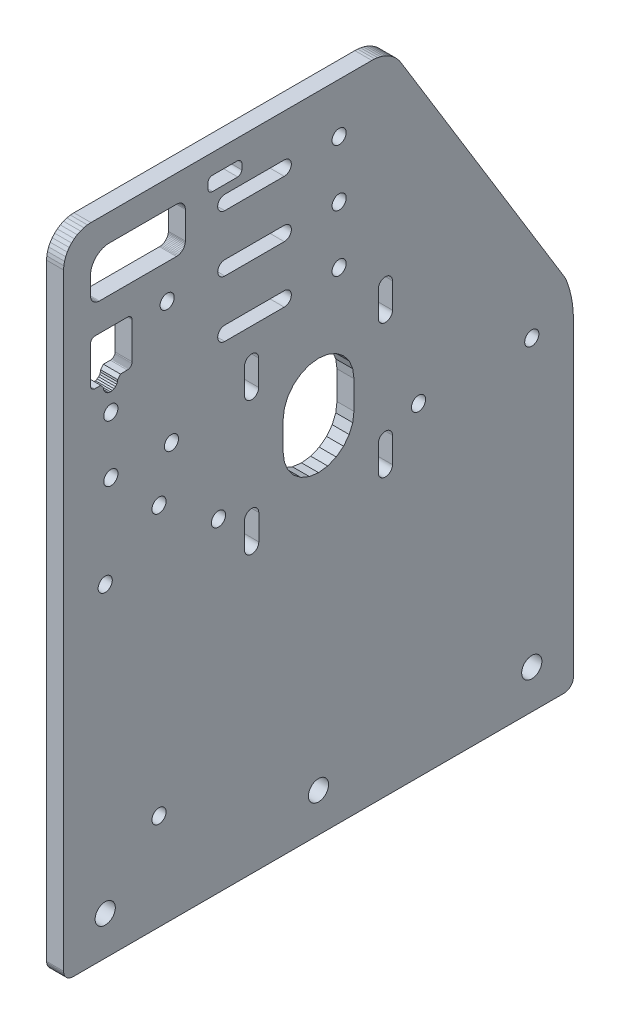
SolidWorks part; units mm, degrees
ref_plane "Front Plane" through (0, 0, 0) normal (0, 0, 1) x (1, 0, 0)
ref_plane "Top Plane" through (0, 0, 0) normal (0, 1, 0) x (1, 0, 0)
ref_plane "Right Plane" through (0, 0, 0) normal (1, 0, 0) x (0, 0, -1)
ref_plane "Plane1" through (0, 0, 0) normal (-1, 0, 0) x (0, -1, 0)
sketch "Sketch1" plane through (0, 0, 0) normal (-1, 0, 0) x (0, -1, 0)
  line L0 (-590.2121, -1614.2437) -> (-495.2304, -1672.3356)
  line L1 (-495.2304, -1672.3356) -> (-492.9855, -1673.1988)
  line L2 (-492.9855, -1673.1988) -> (-490.6881, -1673.9103)
  line L3 (-490.6881, -1673.9103) -> (-488.3483, -1674.4671)
  line L4 (-488.3483, -1674.4671) -> (-485.9766, -1674.8665)
  line L5 (-485.9766, -1674.8665) -> (-483.5835, -1675.1069)
  line L6 (-483.5835, -1675.1069) -> (-481.1798, -1675.1871)
  line L7 (-481.1798, -1675.1871) -> (-371.8266, -1675.1871)
  line L8 (-371.8266, -1675.1871) -> (-371.3877, -1675.1584)
  line L9 (-371.3877, -1675.1584) -> (-370.9562, -1675.0725)
  line L10 (-370.9562, -1675.0725) -> (-370.5397, -1674.9312)
  line L11 (-370.5397, -1674.9312) -> (-370.1452, -1674.7366)
  line L12 (-370.1452, -1674.7366) -> (-369.7795, -1674.4922)
  line L13 (-369.7795, -1674.4922) -> (-369.4487, -1674.2022)
  line L14 (-369.4487, -1674.2022) -> (-369.1587, -1673.8715)
  line L15 (-369.1587, -1673.8715) -> (-368.9143, -1673.5057)
  line L16 (-368.9143, -1673.5057) -> (-368.7198, -1673.1112)
  line L17 (-368.7198, -1673.1112) -> (-368.5784, -1672.6947)
  line L18 (-368.5784, -1672.6947) -> (-368.4926, -1672.2633)
  line L19 (-368.4926, -1672.2633) -> (-368.4638, -1671.8243)
  line L20 (-368.4638, -1671.8243) -> (-368.4638, -1498.5099)
  line L21 (-368.4638, -1498.5099) -> (-368.4926, -1498.071)
  line L22 (-368.4926, -1498.071) -> (-368.5784, -1497.6396)
  line L23 (-368.5784, -1497.6396) -> (-368.7198, -1497.223)
  line L24 (-368.7198, -1497.223) -> (-368.9143, -1496.8285)
  line L25 (-368.9143, -1496.8285) -> (-369.1587, -1496.4628)
  line L26 (-369.1587, -1496.4628) -> (-369.4487, -1496.1321)
  line L27 (-369.4487, -1496.1321) -> (-369.7795, -1495.842)
  line L28 (-369.7795, -1495.842) -> (-370.1452, -1495.5977)
  line L29 (-370.1452, -1495.5977) -> (-370.5397, -1495.4031)
  line L30 (-370.5397, -1495.4031) -> (-370.9562, -1495.2617)
  line L31 (-370.9562, -1495.2617) -> (-371.3877, -1495.1759)
  line L32 (-371.3877, -1495.1759) -> (-371.8266, -1495.1471)
  line L33 (-371.8266, -1495.1471) -> (-586.2881, -1495.1456)
  line L34 (-586.2881, -1495.1456) -> (-587.5497, -1495.2283)
  line L35 (-587.5497, -1495.2283) -> (-588.7897, -1495.475)
  line L36 (-588.7897, -1495.475) -> (-589.987, -1495.8813)
  line L37 (-589.987, -1495.8813) -> (-591.1209, -1496.4405)
  line L38 (-591.1209, -1496.4405) -> (-592.1721, -1497.1429)
  line L39 (-592.1721, -1497.1429) -> (-593.1227, -1497.9766)
  line L40 (-593.1227, -1497.9766) -> (-593.9563, -1498.9271)
  line L41 (-593.9563, -1498.9271) -> (-594.6588, -1499.9784)
  line L42 (-594.6588, -1499.9784) -> (-595.218, -1501.1123)
  line L43 (-595.218, -1501.1123) -> (-595.6244, -1502.3095)
  line L44 (-595.6244, -1502.3095) -> (-595.871, -1503.5495)
  line L45 (-595.871, -1503.5495) -> (-595.9537, -1504.8111)
  line L46 (-595.9537, -1504.8111) -> (-595.9537, -1603.9943)
  line L47 (-595.9537, -1603.9943) -> (-595.9102, -1605.016)
  line L48 (-595.9102, -1605.016) -> (-595.78, -1606.0302)
  line L49 (-595.78, -1606.0302) -> (-595.5641, -1607.0297)
  line L50 (-595.5641, -1607.0297) -> (-595.264, -1608.0073)
  line L51 (-595.264, -1608.0073) -> (-594.8819, -1608.9558)
  line L52 (-594.8819, -1608.9558) -> (-594.4205, -1609.8683)
  line L53 (-594.4205, -1609.8683) -> (-593.8833, -1610.7384)
  line L54 (-593.8833, -1610.7384) -> (-593.274, -1611.5596)
  line L55 (-593.274, -1611.5596) -> (-592.5971, -1612.3261)
  line L56 (-592.5971, -1612.3261) -> (-591.8575, -1613.0323)
  line L57 (-591.8575, -1613.0323) -> (-591.0606, -1613.673)
  line L58 (-591.0606, -1613.673) -> (-590.2121, -1614.2437)
  line L59 (-575.9778, -1552.0841) -> (-575.9778, -1573.0568)
  line L60 (-580.9777, -1573.098) -> (-580.9777, -1552.0841)
  line L61 (-535.9778, -1552.0854) -> (-535.9778, -1573.0582)
  line L62 (-540.9777, -1573.0993) -> (-540.9777, -1552.0854)
  line L63 (-555.9777, -1552.0992) -> (-555.9777, -1573.0855)
  line L64 (-560.9776, -1573.1131) -> (-560.9776, -1552.0992)
  line L65 (-524.9137, -1559.0552) -> (-515.9137, -1559.0552)
  line L66 (-515.9137, -1564.0552) -> (-524.9137, -1564.0552)
  line L67 (-524.9137, -1606.2991) -> (-515.9137, -1606.2991)
  line L68 (-515.9137, -1611.2991) -> (-524.9137, -1611.2991)
  line L69 (-477.6698, -1606.2991) -> (-468.6699, -1606.2991)
  line L70 (-468.6699, -1611.2991) -> (-477.6698, -1611.2991)
  line L71 (-477.6698, -1559.0528) -> (-468.6699, -1559.0552)
  line L72 (-468.6712, -1564.0782) -> (-477.6698, -1564.0758)
  line L73 (-586.0336, -1536.5791) -> (-586.215, -1536.2112)
  line L74 (-586.215, -1536.2112) -> (-586.3468, -1535.8228)
  line L75 (-586.3468, -1535.8228) -> (-586.4269, -1535.4204)
  line L76 (-586.4269, -1535.4204) -> (-586.4537, -1535.0111)
  line L77 (-586.4537, -1535.0111) -> (-586.4537, -1511.2962)
  line L78 (-586.4537, -1511.2962) -> (-586.3968, -1510.4284)
  line L79 (-586.3968, -1510.4284) -> (-586.2271, -1509.5753)
  line L80 (-586.2271, -1509.5753) -> (-585.9476, -1508.7517)
  line L81 (-585.9476, -1508.7517) -> (-585.5629, -1507.9717)
  line L82 (-585.5629, -1507.9717) -> (-585.0797, -1507.2485)
  line L83 (-585.0797, -1507.2485) -> (-584.5062, -1506.5946)
  line L84 (-584.5062, -1506.5946) -> (-583.8523, -1506.0211)
  line L85 (-583.8523, -1506.0211) -> (-583.1291, -1505.5379)
  line L86 (-583.1291, -1505.5379) -> (-582.3491, -1505.1533)
  line L87 (-582.3491, -1505.1533) -> (-581.5255, -1504.8737)
  line L88 (-581.5255, -1504.8737) -> (-580.6725, -1504.704)
  line L89 (-580.6725, -1504.704) -> (-579.8046, -1504.6471)
  line L90 (-579.8046, -1504.6471) -> (-573.6169, -1504.6471)
  line L91 (-573.6169, -1504.6471) -> (-573.2076, -1504.6739)
  line L92 (-573.2076, -1504.6739) -> (-572.8052, -1504.754)
  line L93 (-572.8052, -1504.754) -> (-572.4168, -1504.8858)
  line L94 (-572.4168, -1504.8858) -> (-572.0489, -1505.0673)
  line L95 (-572.0489, -1505.0673) -> (-571.7078, -1505.2952)
  line L96 (-571.7078, -1505.2952) -> (-571.3994, -1505.5656)
  line L97 (-571.3994, -1505.5656) -> (-571.1289, -1505.8741)
  line L98 (-571.1289, -1505.8741) -> (-570.901, -1506.2151)
  line L99 (-570.901, -1506.2151) -> (-570.7196, -1506.583)
  line L100 (-570.7196, -1506.583) -> (-570.5877, -1506.9715)
  line L101 (-570.5877, -1506.9715) -> (-570.5077, -1507.3738)
  line L102 (-570.5077, -1507.3738) -> (-570.4809, -1507.7831)
  line L103 (-570.4809, -1507.7831) -> (-570.4809, -1535.0111)
  line L104 (-570.4809, -1535.0111) -> (-570.5077, -1535.4204)
  line L105 (-570.5077, -1535.4204) -> (-570.5877, -1535.8228)
  line L106 (-570.5877, -1535.8228) -> (-570.7196, -1536.2112)
  line L107 (-570.7196, -1536.2112) -> (-570.901, -1536.5791)
  line L108 (-570.901, -1536.5791) -> (-571.1289, -1536.9202)
  line L109 (-571.1289, -1536.9202) -> (-571.3994, -1537.2286)
  line L110 (-571.3994, -1537.2286) -> (-571.7078, -1537.4991)
  line L111 (-571.7078, -1537.4991) -> (-572.0489, -1537.727)
  line L112 (-572.0489, -1537.727) -> (-572.4168, -1537.9084)
  line L113 (-572.4168, -1537.9084) -> (-572.8052, -1538.0403)
  line L114 (-572.8052, -1538.0403) -> (-573.2076, -1538.1203)
  line L115 (-573.2076, -1538.1203) -> (-573.6169, -1538.1471)
  line L116 (-573.6169, -1538.1471) -> (-583.3177, -1538.1471)
  line L117 (-583.3177, -1538.1471) -> (-583.727, -1538.1203)
  line L118 (-583.727, -1538.1203) -> (-584.1293, -1538.0403)
  line L119 (-584.1293, -1538.0403) -> (-584.5178, -1537.9084)
  line L120 (-584.5178, -1537.9084) -> (-584.8857, -1537.727)
  line L121 (-584.8857, -1537.727) -> (-585.2268, -1537.4991)
  line L122 (-585.2268, -1537.4991) -> (-585.5352, -1537.2286)
  line L123 (-585.5352, -1537.2286) -> (-585.8057, -1536.9202)
  line L124 (-585.8057, -1536.9202) -> (-586.0336, -1536.5791)
  line L125 (-560.5397, -1505.8783) -> (-560.4696, -1505.6715)
  line L126 (-560.4696, -1505.6715) -> (-560.373, -1505.4757)
  line L127 (-560.373, -1505.4757) -> (-560.2517, -1505.2942)
  line L128 (-560.2517, -1505.2942) -> (-560.1078, -1505.1301)
  line L129 (-560.1078, -1505.1301) -> (-559.9436, -1504.9862)
  line L130 (-559.9436, -1504.9862) -> (-559.7621, -1504.8649)
  line L131 (-559.7621, -1504.8649) -> (-559.5663, -1504.7683)
  line L132 (-559.5663, -1504.7683) -> (-559.3596, -1504.6981)
  line L133 (-559.3596, -1504.6981) -> (-559.1312, -1504.6471)
  line L134 (-559.1312, -1504.6471) -> (-558.9276, -1504.6413)
  line L135 (-558.9276, -1504.6413) -> (-548.4809, -1504.6452)
  line L136 (-548.4809, -1504.6452) -> (-545.8818, -1504.6452)
  line L137 (-545.8818, -1504.6452) -> (-545.6677, -1504.6877)
  line L138 (-545.6677, -1504.6877) -> (-545.461, -1504.7579)
  line L139 (-545.461, -1504.7579) -> (-545.2652, -1504.8545)
  line L140 (-545.2652, -1504.8545) -> (-545.0837, -1504.9758)
  line L141 (-545.0837, -1504.9758) -> (-544.9196, -1505.1197)
  line L142 (-544.9196, -1505.1197) -> (-544.7756, -1505.2838)
  line L143 (-544.7756, -1505.2838) -> (-544.6543, -1505.4654)
  line L144 (-544.6543, -1505.4654) -> (-544.5578, -1505.6612)
  line L145 (-544.5578, -1505.6612) -> (-544.4876, -1505.8679)
  line L146 (-544.4876, -1505.8679) -> (-544.445, -1506.082)
  line L147 (-544.445, -1506.082) -> (-544.4414, -1508.2677)
  line L148 (-544.4414, -1508.2677) -> (-543.221, -1509.2377)
  line L149 (-543.221, -1509.2377) -> (-542.574, -1509.3226)
  line L150 (-542.574, -1509.3226) -> (-541.9709, -1509.5721)
  line L151 (-541.9709, -1509.5721) -> (-541.453, -1509.9692)
  line L152 (-541.453, -1509.9692) -> (-541.0555, -1510.4868)
  line L153 (-541.0555, -1510.4868) -> (-540.8055, -1511.0897)
  line L154 (-540.8055, -1511.0897) -> (-540.72, -1511.7367)
  line L155 (-540.72, -1511.7367) -> (-540.805, -1512.3838)
  line L156 (-540.805, -1512.3838) -> (-541.0545, -1512.9868)
  line L157 (-541.0545, -1512.9868) -> (-541.4516, -1513.5047)
  line L158 (-541.4516, -1513.5047) -> (-541.9692, -1513.9022)
  line L159 (-541.9692, -1513.9022) -> (-542.572, -1514.1522)
  line L160 (-542.572, -1514.1522) -> (-543.219, -1514.2377)
  line L161 (-543.219, -1514.2377) -> (-544.4323, -1515.2077)
  line L162 (-544.4323, -1515.2077) -> (-544.4307, -1517.6776)
  line L163 (-544.4307, -1517.6776) -> (-544.4876, -1518.1096)
  line L164 (-544.4876, -1518.1096) -> (-544.5578, -1518.3163)
  line L165 (-544.5578, -1518.3163) -> (-544.6543, -1518.5121)
  line L166 (-544.6543, -1518.5121) -> (-544.7756, -1518.6936)
  line L167 (-544.7756, -1518.6936) -> (-544.9196, -1518.8578)
  line L168 (-544.9196, -1518.8578) -> (-545.0837, -1519.0017)
  line L169 (-545.0837, -1519.0017) -> (-545.2652, -1519.123)
  line L170 (-545.2652, -1519.123) -> (-545.461, -1519.2196)
  line L171 (-545.461, -1519.2196) -> (-545.6677, -1519.2897)
  line L172 (-545.6677, -1519.2897) -> (-546.0997, -1519.3486)
  line L173 (-546.0997, -1519.3486) -> (-558.9578, -1519.3427)
  line L174 (-558.9578, -1519.3427) -> (-559.1455, -1519.3427)
  line L175 (-559.1455, -1519.3427) -> (-559.3596, -1519.3001)
  line L176 (-559.3596, -1519.3001) -> (-559.5663, -1519.23)
  line L177 (-559.5663, -1519.23) -> (-559.7621, -1519.1334)
  line L178 (-559.7621, -1519.1334) -> (-559.9436, -1519.0121)
  line L179 (-559.9436, -1519.0121) -> (-560.1078, -1518.8682)
  line L180 (-560.1078, -1518.8682) -> (-560.2517, -1518.704)
  line L181 (-560.2517, -1518.704) -> (-560.373, -1518.5225)
  line L182 (-560.373, -1518.5225) -> (-560.4696, -1518.3267)
  line L183 (-560.4696, -1518.3267) -> (-560.5397, -1518.12)
  line L184 (-560.5397, -1518.12) -> (-560.5823, -1517.9059)
  line L185 (-560.5823, -1517.9059) -> (-560.5823, -1517.6796)
  line L186 (-560.5823, -1517.6796) -> (-560.568, -1506.084)
  line L187 (-560.568, -1506.084) -> (-560.5397, -1505.8783)
  line L188 (-512.6093, -1578.9371) -> (-510.6228, -1576.3483)
  line L189 (-510.6228, -1576.3483) -> (-508.034, -1574.3618)
  line L190 (-508.034, -1574.3618) -> (-505.0192, -1573.1131)
  line L191 (-505.0192, -1573.1131) -> (-501.784, -1572.6871)
  line L192 (-501.784, -1572.6871) -> (-491.784, -1572.6871)
  line L193 (-491.784, -1572.6871) -> (-488.5487, -1573.1131)
  line L194 (-488.5487, -1573.1131) -> (-485.534, -1574.3618)
  line L195 (-485.534, -1574.3618) -> (-482.9451, -1576.3483)
  line L196 (-482.9451, -1576.3483) -> (-480.9587, -1578.9371)
  line L197 (-480.9587, -1578.9371) -> (-479.7099, -1581.9519)
  line L198 (-479.7099, -1581.9519) -> (-479.284, -1585.1871)
  line L199 (-479.284, -1585.1871) -> (-479.7099, -1588.4224)
  line L200 (-479.7099, -1588.4224) -> (-480.9587, -1591.4371)
  line L201 (-480.9587, -1591.4371) -> (-482.9451, -1594.026)
  line L202 (-482.9451, -1594.026) -> (-485.534, -1596.0125)
  line L203 (-485.534, -1596.0125) -> (-488.5487, -1597.2612)
  line L204 (-488.5487, -1597.2612) -> (-491.784, -1597.6871)
  line L205 (-491.784, -1597.6871) -> (-501.784, -1597.6871)
  line L206 (-501.784, -1597.6871) -> (-505.0192, -1597.2612)
  line L207 (-505.0192, -1597.2612) -> (-508.034, -1596.0125)
  line L208 (-508.034, -1596.0125) -> (-510.6228, -1594.026)
  line L209 (-510.6228, -1594.026) -> (-512.6093, -1591.4371)
  line L210 (-512.6093, -1591.4371) -> (-513.858, -1588.4224)
  line L211 (-513.858, -1588.4224) -> (-514.284, -1585.1871)
  line L212 (-514.284, -1585.1871) -> (-513.858, -1581.9519)
  line L213 (-513.858, -1581.9519) -> (-512.6093, -1578.9371)
  line L214 (-588.9809, -1556.6482) -> (-588.9809, -1547.5504)
  line L215 (-587.544, -1546.1136) -> (-585.6436, -1546.0993)
  line L216 (-583.9746, -1547.7683) -> (-583.9889, -1556.6482)
  line L217 (-585.4257, -1558.085) -> (-587.544, -1558.085)
  arc A0 (-580.9777, -1552.0841) -> (-575.9778, -1552.0841) centre (-578.4777, -1552.0704) cw
  arc A1 (-575.9778, -1573.0568) -> (-580.9777, -1573.098) centre (-578.4777, -1573.0774) cw
  arc A2 (-540.9777, -1552.0854) -> (-535.9778, -1552.0854) centre (-538.4778, -1552.0718) cw
  arc A3 (-535.9778, -1573.0582) -> (-540.9777, -1573.0993) centre (-538.4778, -1573.0787) cw
  arc A4 (-560.9776, -1552.0992) -> (-555.9777, -1552.0992) centre (-558.4777, -1552.0856) cw
  arc A5 (-555.9777, -1573.0855) -> (-560.9776, -1573.1131) centre (-558.4777, -1573.0993) cw
  arc A6 (-515.9137, -1559.0552) -> (-515.9137, -1564.0552) centre (-515.9137, -1561.5552) cw
  arc A7 (-524.9137, -1564.0552) -> (-524.9137, -1559.0552) centre (-524.9137, -1561.5552) cw
  arc A8 (-515.9137, -1606.2991) -> (-515.9137, -1611.2991) centre (-515.9137, -1608.7991) cw
  arc A9 (-524.9137, -1611.2991) -> (-524.9137, -1606.2991) centre (-524.9137, -1608.7991) cw
  arc A10 (-468.6699, -1606.2991) -> (-468.6699, -1611.2991) centre (-468.6699, -1608.7991) cw
  arc A11 (-477.6698, -1611.2991) -> (-477.6698, -1606.2991) centre (-477.6698, -1608.7991) cw
  arc A12 (-468.6699, -1559.0552) -> (-468.6712, -1564.0782) centre (-468.6705, -1561.5667) cw
  arc A13 (-477.6698, -1564.0758) -> (-477.6698, -1559.0528) centre (-477.6692, -1561.5643) cw
  circle A14 centre (-382.1591, -1509.8471) radius 3.5685
  circle A15 centre (-382.1591, -1585.1671) radius 3.5685
  circle A16 centre (-382.1591, -1660.4871) radius 3.5685
  circle A17 centre (-538.3993, -1592.4578) radius 2.5
  circle A18 centre (-558.4485, -1592.4578) radius 2.5
  circle A19 centre (-578.4485, -1592.4578) radius 2.5
  circle A20 centre (-534.4436, -1511.8471) radius 2.5
  circle A21 centre (-558.4024, -1531.723) radius 2.5
  circle A22 centre (-514.4436, -1511.8471) radius 2.5
  circle A23 centre (-514.4436, -1533.239) radius 2.5
  circle A24 centre (-497.4962, -1528.8471) radius 2.5
  circle A25 centre (-482.7991, -1549.8471) radius 2.5
  circle A26 centre (-482.7991, -1509.8471) radius 2.5
  circle A27 centre (-482.7991, -1620.4871) radius 2.5
  circle A28 centre (-482.7991, -1660.4871) radius 2.5
  circle A29 centre (-402.4962, -1528.8471) radius 2.5
  arc A30 (-588.9809, -1547.5504) -> (-587.544, -1546.1136) centre (-587.3137, -1547.7807) cw
  arc A31 (-585.6436, -1546.0993) -> (-583.9746, -1547.7683) centre (-585.6436, -1547.7683) cw
  arc A32 (-583.9889, -1556.6482) -> (-585.4257, -1558.085) centre (-585.656, -1556.4179) cw
  arc A33 (-587.544, -1558.085) -> (-588.9809, -1556.6482) centre (-587.3262, -1556.4303) cw
extrude "Boss-Extrude1" add sketch "Sketch1" against normal blind 6
